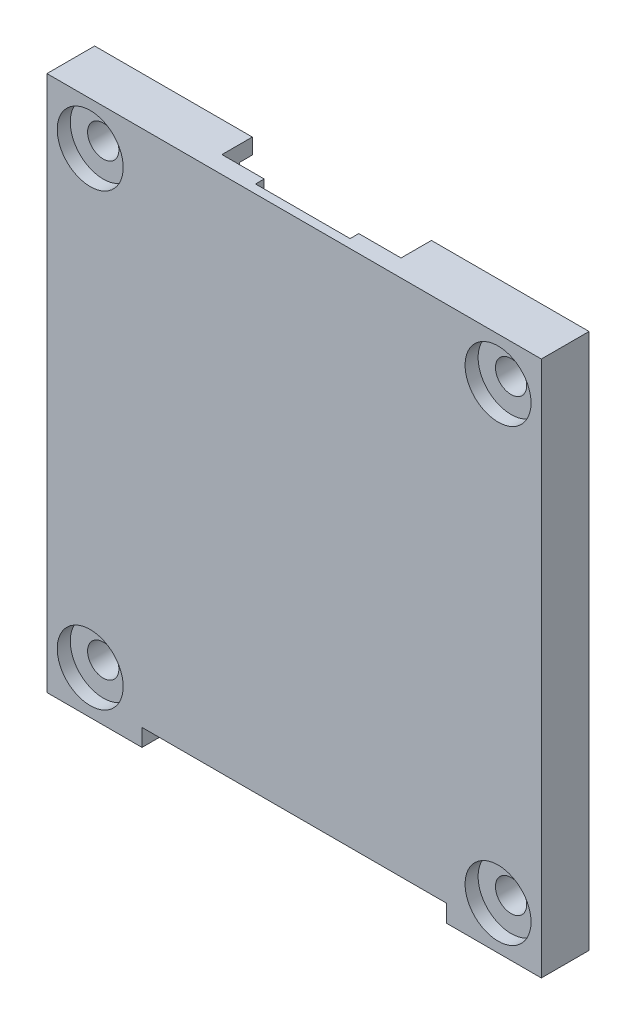
SolidWorks part; units mm, degrees
ref_plane "前视基准面" through (0, 0, 0) normal (0, 0, 1) x (1, 0, 0)
ref_plane "上视基准面" through (0, 0, 0) normal (0, 1, 0) x (1, 0, 0)
ref_plane "右视基准面" through (0, 0, 0) normal (1, 0, 0) x (0, 0, -1)
other "Configuration Table"
sketch "草图1" plane through (0, 0, 0) normal (0, 0, 1) x (1, 0, 0)
  line L1 (-24.5491, 28.8784) -> (32.4256, 28.8784)
  line L2 (-24.5491, 28.8784) -> (-24.5491, -32.8963)
  line L3 (-24.5491, -32.8963) -> (32.4256, -32.8963)
  line L4 (32.4256, 28.8784) -> (32.4256, -32.8963)
  dimension "D1" = 2
  dimension "D2" = 2
  dimension "D3" = 2
  dimension "D4" = 2
extrude "凸台-拉伸1" add sketch "草图1" along normal blind 4
sketch "草图2" plane through (0, 0, 0) normal (0, 0, -1) x (-1, 0, 0)
  line L0 (-14.2579, 28.8784) -> (-9.3875, 28.8784)
  line L1 (-32.4256, 28.8784) -> (24.5491, 28.8784) construction
  line L2 (-9.3875, 28.8784) -> (-9.3875, 24.5138) construction
  line L3 (-9.3875, 28.8784) -> (-9.3875, 24.5138)
  line L5 (-14.2579, 24.5138) -> (-14.2579, 28.8784)
  line L6 (1.511, 28.8784) -> (6.3814, 28.8784)
  line L7 (1.511, 28.8784) -> (1.511, 24.4884) construction
  line L8 (6.3814, 24.4884) -> (6.3814, 28.8784) construction
  line L9 (6.3814, 28.8784) -> (6.3814, 24.4884)
  line L11 (1.511, 24.4884) -> (1.511, 28.8784)
  line L12 (-10.1009, 23.8082) -> (-10.1009, 21.974) construction
  line L14 (1.9244, 24.0844) -> (1.9244, 21.5978)
  line L15 (1.9244, 21.5978) -> (6.1991, 21.5978)
  line L16 (6.1991, 24.0844) -> (6.1991, 21.5978)
  line L18 (-14.0756, 24.0844) -> (-14.0756, 21.5978)
  line L19 (-14.0756, 21.5978) -> (-9.8009, 21.5978)
  line L20 (-9.8009, 24.0844) -> (-9.8009, 21.5978)
  line L21 (-13.7756, 21.974) -> (-13.7756, 23.8082) construction
  line L22 (-10.1771, 21.8978) -> (-11.4621, 21.8978) construction
  line L26 (5.8229, 21.8978) -> (4.538, 21.8978) construction
  line L29 (1.9244, 24.0844) -> (6.1991, 24.0844)
  line L30 (2.3006, 23.8844) -> (3.5856, 23.8844) construction
  line L31 (1.511, 24.4884) -> (6.3814, 24.4884)
  line L32 (3.743, 24.6884) -> (2.219, 24.6884) construction
  line L33 (2.2244, 21.974) -> (2.2244, 23.8082) construction
  line L34 (5.8991, 23.8082) -> (5.8991, 21.974) construction
  line L35 (-14.0756, 24.0844) -> (-9.8009, 24.0844)
  line L36 (-13.6994, 23.8844) -> (-12.4145, 23.8844) construction
  line L37 (-14.2579, 24.5138) -> (-9.3875, 24.5138)
  dimension "D1" = 0.3
  dimension "D2" = 0.3
  dimension "D3" = 0.3
  dimension "D4" = 0.2
  dimension "D5" = 0.2
  dimension "D6" = 0.3
  dimension "D7" = 0.3
  dimension "D8" = 0.3
  dimension "D9" = 0.2
extrude "切除-拉伸1" cut sketch "草图2" along normal blind 0.2 and the other way blind 2
sketch "草图3" plane through (0, 0, 0) normal (0, 0, -1) x (-1, 0, 0)
  line L1 (-9.3875, 20.2641) -> (1.511, 20.2641)
  line L3 (-2.8028, 20.5641) -> (-5.0888, 20.5641) construction
  line L7 (-9.3875, 20.2641) -> (-9.3875, 28.8784)
  line L8 (-9.3875, 28.8784) -> (1.511, 28.8784)
  line L9 (1.511, 28.8784) -> (1.511, 20.2641)
  dimension "D1" = 0.3
extrude "切除-拉伸2" cut sketch "草图3" against normal blind 3
sketch "草图4" plane through (0, 0, 0) normal (0, 0, -1) x (-1, 0, 0)
  line L0 (-8.8148, 20.2641) -> (-8.8148, 14.9345)
  line L1 (-9.3875, 20.2641) -> (1.511, 20.2641) construction
  line L2 (-8.8148, 14.9345) -> (0.9383, 14.9345)
  line L3 (0.9383, 14.9345) -> (0.9383, 20.2641)
  line L4 (0.9383, 20.2641) -> (-8.8148, 20.2641)
  line L5 (-8.5148, 18.6911) -> (-8.5148, 15.4911) construction
  line L6 (0.6383, 15.4911) -> (0.6383, 16.4024) construction
  line L7 (-0.6382, 15.2345) -> (0.3818, 15.2345) construction
  dimension "D1" = 0.3
  dimension "D2" = 0.3
  dimension "D3" = 0.3
extrude "切除-拉伸3" cut sketch "草图4" against normal blind 2
sketch "草图5" plane through (0, 0, 0) normal (0, 0, -1) x (-1, 0, 0)
  circle A0 centre (-22.4383, 24.3411) radius 1.0565 construction
  circle A1 centre (-17.4383, 24.3411) radius 1.0565 construction
  circle A2 centre (-23.4383, 21.841) radius 1.1565 construction
  circle A3 centre (-16.4383, 21.841) radius 1.1565 construction
  circle A4 centre (9.5618, 24.3411) radius 1.0565 construction
  circle A5 centre (14.5618, 24.3411) radius 1.0565 construction
  circle A6 centre (8.5618, 21.841) radius 1.1565 construction
  circle A7 centre (15.5618, 21.841) radius 1.1565 construction
  circle A8 centre (-22.4383, 24.3411) radius 1.35
  circle A9 centre (-23.4383, 21.841) radius 1.5
  circle A10 centre (-17.4383, 24.3411) radius 1.35
  circle A11 centre (-16.4383, 21.841) radius 1.5
  circle A12 centre (9.5618, 24.3411) radius 1.35
  circle A13 centre (8.5618, 21.841) radius 1.5
  circle A14 centre (14.5618, 24.3411) radius 1.35
  circle A15 centre (15.5618, 21.841) radius 1.5
  dimension "D1" = 2.7
  dimension "D2" = 3
  dimension "D3" = 2.7
  dimension "D4" = 3
  dimension "D5" = 2.7
  dimension "D6" = 2.7
  dimension "D7" = 3
  dimension "D8" = 3
extrude "切除-拉伸4" cut sketch "草图5" against normal blind 2 contours A11 A10 | A10 A11 | A10 A11 | A9 A8 | A8 A9 | A8 A9 | A13 A12 | A15 A14 | A12 A13 | A12 A13 | A14 A15 | A14 A15
sketch "草图6" plane through (0, 0, 0) normal (0, 0, -1) x (-1, 0, 0)
  line L1 (19.3218, 20.1001) -> (22.5491, 20.1001)
  line L2 (19.3218, 20.1001) -> (19.3218, -1.154)
  line L3 (19.3218, -1.154) -> (22.5491, -1.154)
  line L4 (22.5491, 20.1001) -> (22.5491, -1.154)
  line L5 (-30.4256, 20.1001) -> (-27.1983, 20.1001)
  line L6 (-30.4256, 20.1001) -> (-30.4256, -1.154)
  line L7 (-30.4256, -1.154) -> (-27.1983, -1.154)
  line L8 (-27.1983, 20.1001) -> (-27.1983, -1.154)
extrude "切除-拉伸5" cut sketch "草图6" against normal blind 2
sketch "草图7" plane through (0, 0, 0) normal (0, 0, -1) x (-1, 0, 0)
  line L0 (6.711, -30.5278) -> (6.711, -29.2577) construction
  line L1 (9.538, -25.4157) -> (10.8229, -25.4157) construction
  line L2 (11.2048, -13.659) -> (12.4048, -13.659)
  line L3 (12.4048, -12.5589) -> (11.2048, -12.5589)
  line L4 (11.2048, -13.659) -> (12.4048, -13.659) construction
  line L5 (12.4048, -12.5589) -> (11.2048, -12.5589) construction
  line L6 (11.2048, -18.459) -> (12.4048, -18.459)
  line L7 (12.4048, -17.359) -> (11.2048, -17.359)
  line L8 (11.2048, -18.459) -> (12.4048, -18.459) construction
  line L9 (12.4048, -17.359) -> (11.2048, -17.359) construction
  line L10 (11.2048, -23.259) -> (12.4048, -23.259)
  line L11 (12.4048, -22.159) -> (11.2048, -22.159)
  line L12 (11.2048, -23.259) -> (12.4048, -23.259) construction
  line L13 (12.4048, -22.159) -> (11.2048, -22.159) construction
  line L14 (7.3006, -25.4157) -> (8.5856, -25.4157) construction
  line L15 (8.5856, -27.4023) -> (7.3006, -27.4023) construction
  line L16 (13.4048, -21.859) -> (10.2048, -21.859)
  line L17 (13.4048, -23.559) -> (13.4048, -21.859)
  line L18 (10.2048, -23.559) -> (13.4048, -23.559)
  line L19 (10.2048, -21.859) -> (10.2048, -23.559)
  line L20 (13.4048, -21.859) -> (10.2048, -21.859)
  line L21 (13.4048, -23.559) -> (13.4048, -21.859)
  line L22 (10.2048, -23.559) -> (13.4048, -23.559)
  line L23 (10.2048, -21.859) -> (10.2048, -23.559)
  line L24 (13.4048, -17.059) -> (10.2048, -17.059)
  line L25 (13.4048, -18.759) -> (13.4048, -17.059)
  line L26 (10.2048, -18.759) -> (13.4048, -18.759)
  line L27 (10.2048, -17.059) -> (10.2048, -18.759)
  line L28 (13.4048, -17.059) -> (10.2048, -17.059)
  line L29 (13.4048, -18.759) -> (13.4048, -17.059)
  line L30 (10.2048, -18.759) -> (13.4048, -18.759)
  line L31 (10.2048, -17.059) -> (10.2048, -18.759)
  line L32 (13.4048, -12.2589) -> (10.2048, -12.2589)
  line L33 (13.4048, -13.959) -> (13.4048, -12.2589)
  line L34 (10.2048, -13.959) -> (13.4048, -13.959)
  line L35 (10.2048, -12.2589) -> (10.2048, -13.959)
  line L36 (13.4048, -12.2589) -> (10.2048, -12.2589)
  line L37 (13.4048, -13.959) -> (13.4048, -12.2589)
  line L38 (10.2048, -13.959) -> (13.4048, -13.959)
  line L39 (10.2048, -12.2589) -> (10.2048, -13.959)
  line L40 (7.2244, -27.3261) -> (7.2244, -25.4919) construction
  line L41 (10.8991, -25.4919) -> (10.8991, -27.3261) construction
  line L42 (11.1814, -28.8767) -> (11.1814, -30.8963) construction
  line L43 (9.505, -28.7497) -> (11.0544, -28.7497) construction
  line L44 (7.2444, -28.7243) -> (8.7176, -28.7243) construction
  line L45 (-18.6994, -25.4157) -> (-17.4145, -25.4157) construction
  line L46 (-18.7756, -27.3261) -> (-18.7756, -25.4919) construction
  line L47 (-15.1009, -25.4919) -> (-15.1009, -27.3261) construction
  line L48 (-17.4145, -27.4023) -> (-18.6994, -27.4023) construction
  line L49 (-16.6195, -28.7523) -> (-15.0955, -28.7523) construction
  line L50 (-19.0579, -30.8963) -> (-19.0579, -28.8793) construction
  line L51 (-14.5875, -29.2603) -> (-14.5875, -30.5303) construction
  line L52 (6.711, -30.5278) -> (6.711, -29.2577)
  line L53 (9.538, -25.4157) -> (10.8229, -25.4157)
  line L54 (7.3006, -25.4157) -> (8.5856, -25.4157)
  line L55 (8.5856, -27.4023) -> (7.3006, -27.4023)
  line L56 (7.2244, -27.3261) -> (7.2244, -25.4919)
  line L57 (10.8991, -25.4919) -> (10.8991, -27.3261)
  line L58 (11.1814, -28.8767) -> (11.1814, -30.8963)
  line L59 (9.505, -28.7497) -> (11.0544, -28.7497)
  line L60 (7.2444, -28.7243) -> (8.7176, -28.7243)
  line L61 (-18.6994, -25.4157) -> (-17.4145, -25.4157)
  line L62 (-18.7756, -27.3261) -> (-18.7756, -25.4919)
  line L63 (-15.1009, -25.4919) -> (-15.1009, -27.3261)
  line L64 (-17.4145, -27.4023) -> (-18.6994, -27.4023)
  line L65 (-16.6195, -28.7523) -> (-15.0955, -28.7523)
  line L66 (-19.0579, -30.8963) -> (-19.0579, -28.8793)
  line L67 (-14.5875, -29.2603) -> (-14.5875, -30.5303)
  circle A1 centre (11.0544, -4.4087) radius 0.9
  circle A2 centre (11.0544, -4.4087) radius 0.9
  circle A3 centre (-1.4384, -17.8159) radius 1.55
  circle A4 centre (-1.4384, -17.8159) radius 1.55
  circle A5 centre (11.0544, -9.4088) radius 0.9
  circle A6 centre (11.0544, -9.4088) radius 0.9
  circle A7 centre (-6.4382, -17.816) radius 1.55
  circle A8 centre (-6.4382, -17.816) radius 1.55
  circle A12 centre (-9.4382, -27.816) radius 1.3
  circle A13 centre (1.5618, -27.816) radius 1.3
  spline S0 degree 2 poles (1678.0415, 1065.4937) (11.9563, -51.0686) (-2.5809, -18.3227) (-2.6751, -18.1106) (-2.6867, -17.8776) (-2.6983, -17.6458) (-2.6253, -17.4243) (-2.5527, -17.2039) (-2.4049, -17.0235) (-2.2578, -16.8439) (-2.055, -16.7288) (-1.8532, -16.6142) (-1.6226, -16.5797) (-1.393, -16.5453) (-1.1654, -16.5961) (33.6716, -24.3719) (-710.0576, -1886.511) knots -19.102519 -19.102519 -19.102519 0.125 0.125 0.25 0.25 0.375 0.375 0.5 0.5 0.625 0.625 0.75 0.75 0.875 0.875 20.074642 20.074642 20.074642 only from (-2.3221, -18.6999) to (-0.7448, -16.776) construction
  spline S1 degree 2 poles (1902.7481, -608.804) (-22.9104, -49.606) (-7.5673, -17.2795) (-7.475, -17.0851) (-7.3221, -16.9321) (-7.17, -16.7799) (-6.9747, -16.687) (25.2074, -1.3776) (613.4226, -1917.7837) knots -41.164672 -41.164672 -41.164672 0.25 0.25 0.5 0.5 0.75 0.75 42.09914 42.09914 42.09914 only from (-7.6818, -17.689) to (-6.5652, -16.5725) construction
  spline S2 degree 2 poles (2950.6338, 591.2484) (-0.0165, 21.11) (10.5998, -4.6) (10.6376, -4.6914) (10.7082, -4.7622) (10.7781, -4.8322) (10.8704, -4.8706) (10.9618, -4.9086) (11.0618, -4.9087) (11.1607, -4.9088) (11.2531, -4.8706) (11.3445, -4.8329) (11.4153, -4.7622) (11.4854, -4.6924) (11.5237, -4.6) (22.1068, 20.8706) (-2910.0665, 675.7824) knots -34.741877 -34.741877 -34.741877 0.125 0.125 0.25 0.25 0.375 0.375 0.5 0.5 0.625 0.625 0.75 0.75 0.875 0.875 35.632733 35.632733 35.632733 only from (10.5618, -4.4087) to (11.5618, -4.4087)
  spline S3 degree 2 poles (-2928.5103, -600.0658) (22.1401, -29.9274) (11.5237, -4.2173) (11.486, -4.1259) (11.4153, -4.0551) (11.3455, -3.9851) (11.2531, -3.9467) (11.1618, -3.9088) (11.0618, -3.9087) (10.9629, -3.9086) (10.8704, -3.9467) (10.779, -3.9845) (10.7082, -4.0551) (10.6382, -4.125) (10.5998, -4.2173) (0.0167, -29.6879) (2932.1901, -684.5997) knots -34.741877 -34.741877 -34.741877 0.125 0.125 0.25 0.25 0.375 0.375 0.5 0.5 0.625 0.625 0.75 0.75 0.875 0.875 35.632733 35.632733 35.632733 only from (11.5618, -4.4087) to (10.5618, -4.4087)
  spline S4 degree 2 poles (10.5618, -4.4087) (10.5618, -4.5078) (10.5998, -4.6) (10.6376, -4.6914) (10.7082, -4.7622) (10.7781, -4.8322) (10.8704, -4.8706) (10.9618, -4.9086) (11.0618, -4.9087) (11.1607, -4.9088) (11.2531, -4.8706) (11.3445, -4.8329) (11.4153, -4.7622) (11.4854, -4.6924) (11.5237, -4.6) (11.5618, -4.5084) (11.5618, -4.4087) knots 0 0 0 0.125 0.125 0.25 0.25 0.375 0.375 0.5 0.5 0.625 0.625 0.75 0.75 0.875 0.875 1 1 1 construction
  spline S5 degree 2 poles (11.5618, -4.4087) (11.5618, -4.3095) (11.5237, -4.2173) (11.486, -4.1259) (11.4153, -4.0551) (11.3455, -3.9851) (11.2531, -3.9467) (11.1618, -3.9088) (11.0618, -3.9087) (10.9629, -3.9086) (10.8704, -3.9467) (10.779, -3.9845) (10.7082, -4.0551) (10.6382, -4.125) (10.5998, -4.2173) (10.5618, -4.3089) (10.5618, -4.4087) knots 0 0 0 0.125 0.125 0.25 0.25 0.375 0.375 0.5 0.5 0.625 0.625 0.75 0.75 0.875 0.875 1 1 1 construction
  spline S6 degree 2 poles (2950.6338, 586.2483) (-0.0165, 16.1099) (10.5998, -9.6001) (10.6376, -9.6915) (10.7082, -9.7623) (10.7781, -9.8323) (10.8704, -9.8707) (10.9618, -9.9087) (11.0618, -9.9088) (11.1607, -9.9089) (11.2531, -9.8707) (11.3445, -9.833) (11.4153, -9.7623) (11.4854, -9.6925) (11.5237, -9.6001) (22.1068, 15.8705) (-2910.0665, 670.7823) knots -34.741877 -34.741877 -34.741877 0.125 0.125 0.25 0.25 0.375 0.375 0.5 0.5 0.625 0.625 0.75 0.75 0.875 0.875 35.632733 35.632733 35.632733 only from (10.5618, -9.4088) to (11.5618, -9.4088)
  spline S7 degree 2 poles (-2928.5103, -605.0659) (22.1401, -34.9275) (11.5237, -9.2174) (11.486, -9.126) (11.4153, -9.0552) (11.3455, -8.9852) (11.2531, -8.9468) (11.1618, -8.9089) (11.0618, -8.9088) (10.9629, -8.9087) (10.8704, -8.9468) (10.779, -8.9846) (10.7082, -9.0552) (10.6382, -9.1251) (10.5998, -9.2174) (0.0167, -34.688) (2932.1901, -689.5998) knots -34.741877 -34.741877 -34.741877 0.125 0.125 0.25 0.25 0.375 0.375 0.5 0.5 0.625 0.625 0.75 0.75 0.875 0.875 35.632733 35.632733 35.632733 only from (11.5618, -9.4088) to (10.5618, -9.4088)
  spline S8 degree 2 poles (10.5618, -9.4088) (10.5618, -9.5079) (10.5998, -9.6001) (10.6376, -9.6915) (10.7082, -9.7623) (10.7781, -9.8323) (10.8704, -9.8707) (10.9618, -9.9087) (11.0618, -9.9088) (11.1607, -9.9089) (11.2531, -9.8707) (11.3445, -9.833) (11.4153, -9.7623) (11.4854, -9.6925) (11.5237, -9.6001) (11.5618, -9.5085) (11.5618, -9.4088) knots 0 0 0 0.125 0.125 0.25 0.25 0.375 0.375 0.5 0.5 0.625 0.625 0.75 0.75 0.875 0.875 1 1 1 construction
  spline S9 degree 2 poles (11.5618, -9.4088) (11.5618, -9.3096) (11.5237, -9.2174) (11.486, -9.126) (11.4153, -9.0552) (11.3455, -8.9852) (11.2531, -8.9468) (11.1618, -8.9089) (11.0618, -8.9088) (10.9629, -8.9087) (10.8704, -8.9468) (10.779, -8.9846) (10.7082, -9.0552) (10.6382, -9.1251) (10.5998, -9.2174) (10.5618, -9.309) (10.5618, -9.4088) knots 0 0 0 0.125 0.125 0.25 0.25 0.375 0.375 0.5 0.5 0.625 0.625 0.75 0.75 0.875 0.875 1 1 1 construction
  spline S10 degree 2 poles (-589.7302, 2925.0534) (-14.3408, -24.7511) (12.6153, -13.6171) (12.7159, -13.5755) (12.7937, -13.4979) (12.8708, -13.421) (12.9129, -13.3194) (12.9547, -13.2189) (12.9548, -13.1089) (12.9549, -13.0001) (12.9129, -12.8985) (12.8714, -12.7979) (12.7937, -12.72) (12.7168, -12.643) (12.6153, -12.6008) (-14.1125, -1.4985) (-666.5698, -2934.5065) knots -33.117037 -33.117037 -33.117037 0.125 0.125 0.25 0.25 0.375 0.375 0.5 0.5 0.625 0.625 0.75 0.75 0.875 0.875 34.022438 34.022438 34.022438 only from (12.4048, -13.659) to (12.4048, -12.5589)
  spline S11 degree 2 poles (613.3398, -2951.2713) (37.9504, -1.4668) (10.9943, -12.6008) (10.8937, -12.6424) (10.8159, -12.72) (10.7389, -12.7969) (10.6967, -12.8985) (10.6549, -12.999) (10.6548, -13.1089) (10.6547, -13.2178) (10.6967, -13.3194) (10.7382, -13.42) (10.8159, -13.4979) (10.8928, -13.5749) (10.9943, -13.6171) (37.7221, -24.7194) (690.1794, 2908.2886) knots -33.117037 -33.117037 -33.117037 0.125 0.125 0.25 0.25 0.375 0.375 0.5 0.5 0.625 0.625 0.75 0.75 0.875 0.875 34.022438 34.022438 34.022438 only from (11.2048, -12.5589) to (11.2048, -13.659)
  spline S12 degree 2 poles (12.4048, -13.659) (12.5139, -13.659) (12.6153, -13.6171) (12.7159, -13.5755) (12.7937, -13.4979) (12.8708, -13.421) (12.9129, -13.3194) (12.9547, -13.2189) (12.9548, -13.1089) (12.9549, -13.0001) (12.9129, -12.8985) (12.8714, -12.7979) (12.7937, -12.72) (12.7168, -12.643) (12.6153, -12.6008) (12.5145, -12.5589) (12.4048, -12.5589) knots 0 0 0 0.125 0.125 0.25 0.25 0.375 0.375 0.5 0.5 0.625 0.625 0.75 0.75 0.875 0.875 1 1 1 construction
  spline S13 degree 2 poles (11.2048, -12.5589) (11.0957, -12.5589) (10.9943, -12.6008) (10.8937, -12.6424) (10.8159, -12.72) (10.7389, -12.7969) (10.6967, -12.8985) (10.6549, -12.999) (10.6548, -13.1089) (10.6547, -13.2178) (10.6967, -13.3194) (10.7382, -13.42) (10.8159, -13.4979) (10.8928, -13.5749) (10.9943, -13.6171) (11.0951, -13.659) (11.2048, -13.659) knots 0 0 0 0.125 0.125 0.25 0.25 0.375 0.375 0.5 0.5 0.625 0.625 0.75 0.75 0.875 0.875 1 1 1 construction
  spline S14 degree 2 poles (-589.7302, 2920.2534) (-14.3408, -29.5511) (12.6153, -18.4171) (12.7159, -18.3756) (12.7937, -18.2979) (12.8708, -18.221) (12.9129, -18.1195) (12.9547, -18.0189) (12.9548, -17.909) (12.9549, -17.8001) (12.9129, -17.6985) (12.8714, -17.5979) (12.7937, -17.5201) (12.7168, -17.443) (12.6153, -17.4008) (-14.1125, -6.2985) (-666.5698, -2939.3065) knots -33.117037 -33.117037 -33.117037 0.125 0.125 0.25 0.25 0.375 0.375 0.5 0.5 0.625 0.625 0.75 0.75 0.875 0.875 34.022438 34.022438 34.022438 only from (12.4048, -18.459) to (12.4048, -17.359)
  spline S15 degree 2 poles (613.3398, -2956.0713) (37.9504, -6.2668) (10.9943, -17.4008) (10.8937, -17.4424) (10.8159, -17.5201) (10.7389, -17.5969) (10.6967, -17.6985) (10.6549, -17.799) (10.6548, -17.909) (10.6547, -18.0178) (10.6967, -18.1195) (10.7382, -18.2201) (10.8159, -18.2979) (10.8928, -18.3749) (10.9943, -18.4171) (37.7221, -29.5194) (690.1794, 2903.4885) knots -33.117037 -33.117037 -33.117037 0.125 0.125 0.25 0.25 0.375 0.375 0.5 0.5 0.625 0.625 0.75 0.75 0.875 0.875 34.022438 34.022438 34.022438 only from (11.2048, -17.359) to (11.2048, -18.459)
  spline S16 degree 2 poles (12.4048, -18.459) (12.5139, -18.459) (12.6153, -18.4171) (12.7159, -18.3756) (12.7937, -18.2979) (12.8708, -18.221) (12.9129, -18.1195) (12.9547, -18.0189) (12.9548, -17.909) (12.9549, -17.8001) (12.9129, -17.6985) (12.8714, -17.5979) (12.7937, -17.5201) (12.7168, -17.443) (12.6153, -17.4008) (12.5145, -17.359) (12.4048, -17.359) knots 0 0 0 0.125 0.125 0.25 0.25 0.375 0.375 0.5 0.5 0.625 0.625 0.75 0.75 0.875 0.875 1 1 1 construction
  spline S17 degree 2 poles (11.2048, -17.359) (11.0957, -17.359) (10.9943, -17.4008) (10.8937, -17.4424) (10.8159, -17.5201) (10.7389, -17.5969) (10.6967, -17.6985) (10.6549, -17.799) (10.6548, -17.909) (10.6547, -18.0178) (10.6967, -18.1195) (10.7382, -18.2201) (10.8159, -18.2979) (10.8928, -18.3749) (10.9943, -18.4171) (11.0951, -18.459) (11.2048, -18.459) knots 0 0 0 0.125 0.125 0.25 0.25 0.375 0.375 0.5 0.5 0.625 0.625 0.75 0.75 0.875 0.875 1 1 1 construction
  spline S18 degree 2 poles (-589.7302, 2915.4534) (-14.3408, -34.3511) (12.6153, -23.2171) (12.7159, -23.1756) (12.7937, -23.0979) (12.8708, -23.021) (12.9129, -22.9195) (12.9547, -22.8189) (12.9548, -22.709) (12.9549, -22.6001) (12.9129, -22.4985) (12.8714, -22.3979) (12.7937, -22.3201) (12.7168, -22.243) (12.6153, -22.2008) (-14.1125, -11.0985) (-666.5698, -2944.1065) knots -33.117037 -33.117037 -33.117037 0.125 0.125 0.25 0.25 0.375 0.375 0.5 0.5 0.625 0.625 0.75 0.75 0.875 0.875 34.022438 34.022438 34.022438 only from (12.4048, -23.259) to (12.4048, -22.159)
  spline S19 degree 2 poles (613.3398, -2960.8713) (37.9504, -11.0668) (10.9943, -22.2008) (10.8937, -22.2424) (10.8159, -22.3201) (10.7389, -22.3969) (10.6967, -22.4985) (10.6549, -22.599) (10.6548, -22.709) (10.6547, -22.8178) (10.6967, -22.9195) (10.7382, -23.0201) (10.8159, -23.0979) (10.8928, -23.1749) (10.9943, -23.2171) (37.7221, -34.3194) (690.1794, 2898.6885) knots -33.117037 -33.117037 -33.117037 0.125 0.125 0.25 0.25 0.375 0.375 0.5 0.5 0.625 0.625 0.75 0.75 0.875 0.875 34.022438 34.022438 34.022438 only from (11.2048, -22.159) to (11.2048, -23.259)
  spline S20 degree 2 poles (12.4048, -23.259) (12.5139, -23.259) (12.6153, -23.2171) (12.7159, -23.1756) (12.7937, -23.0979) (12.8708, -23.021) (12.9129, -22.9195) (12.9547, -22.8189) (12.9548, -22.709) (12.9549, -22.6001) (12.9129, -22.4985) (12.8714, -22.3979) (12.7937, -22.3201) (12.7168, -22.243) (12.6153, -22.2008) (12.5145, -22.159) (12.4048, -22.159) knots 0 0 0 0.125 0.125 0.25 0.25 0.375 0.375 0.5 0.5 0.625 0.625 0.75 0.75 0.875 0.875 1 1 1 construction
  spline S21 degree 2 poles (11.2048, -22.159) (11.0957, -22.159) (10.9943, -22.2008) (10.8937, -22.2424) (10.8159, -22.3201) (10.7389, -22.3969) (10.6967, -22.4985) (10.6549, -22.599) (10.6548, -22.709) (10.6547, -22.8178) (10.6967, -22.9195) (10.7382, -23.0201) (10.8159, -23.0979) (10.8928, -23.1749) (10.9943, -23.2171) (11.0951, -23.259) (11.2048, -23.259) knots 0 0 0 0.125 0.125 0.25 0.25 0.375 0.375 0.5 0.5 0.625 0.625 0.75 0.75 0.875 0.875 1 1 1 construction
  spline S22 degree 2 poles (2922.4089, 651.7628) (-13.4862, 6.1019) (0.7303, -28.1604) (0.7991, -28.3263) (0.9254, -28.4524) (1.0524, -28.5793) (1.2173, -28.6475) (1.3833, -28.7161) (1.5618, -28.716) (1.7413, -28.7159) (1.9062, -28.6475) (2.072, -28.5787) (2.1981, -28.4524) (2.325, -28.3253) (2.3932, -28.1604) (16.635, 6.2818) (-2929.7513, 604.884) knots -25.81424 -25.81424 -25.81424 0.125 0.125 0.25 0.25 0.375 0.375 0.5 0.5 0.625 0.625 0.75 0.75 0.875 0.875 26.860433 26.860433 26.860433 only from (0.6618, -27.816) to (2.4618, -27.816)
  spline S23 degree 2 poles (-2919.2854, -707.3948) (16.6097, -61.7339) (2.3932, -27.4716) (2.3244, -27.3057) (2.1981, -27.1796) (2.0711, -27.0527) (1.9062, -26.9845) (1.7402, -26.9159) (1.5618, -26.916) (1.3822, -26.9161) (1.2173, -26.9845) (1.0515, -27.0533) (0.9254, -27.1796) (0.7985, -27.3067) (0.7303, -27.4716) (-13.5115, -61.9138) (2932.8748, -660.516) knots -25.81424 -25.81424 -25.81424 0.125 0.125 0.25 0.25 0.375 0.375 0.5 0.5 0.625 0.625 0.75 0.75 0.875 0.875 26.860433 26.860433 26.860433 only from (2.4618, -27.816) to (0.6618, -27.816)
  spline S24 degree 2 poles (0.6618, -27.816) (0.6618, -27.9953) (0.7303, -28.1604) (0.7991, -28.3263) (0.9254, -28.4524) (1.0524, -28.5793) (1.2173, -28.6475) (1.3833, -28.7161) (1.5618, -28.716) (1.7413, -28.7159) (1.9062, -28.6475) (2.072, -28.5787) (2.1981, -28.4524) (2.325, -28.3253) (2.3932, -28.1604) (2.4618, -27.9947) (2.4618, -27.816) knots 0 0 0 0.125 0.125 0.25 0.25 0.375 0.375 0.5 0.5 0.625 0.625 0.75 0.75 0.875 0.875 1 1 1 construction
  spline S25 degree 2 poles (2.4618, -27.816) (2.4618, -27.6367) (2.3932, -27.4716) (2.3244, -27.3057) (2.1981, -27.1796) (2.0711, -27.0527) (1.9062, -26.9845) (1.7402, -26.9159) (1.5618, -26.916) (1.3822, -26.9161) (1.2173, -26.9845) (1.0515, -27.0533) (0.9254, -27.1796) (0.7985, -27.3067) (0.7303, -27.4716) (0.6618, -27.6373) (0.6618, -27.816) knots 0 0 0 0.125 0.125 0.25 0.25 0.375 0.375 0.5 0.5 0.625 0.625 0.75 0.75 0.875 0.875 1 1 1 construction
  spline S26 degree 2 poles (2911.4089, 651.7628) (-24.4862, 6.1019) (-10.2697, -28.1604) (-10.2009, -28.3263) (-10.0746, -28.4524) (-9.9476, -28.5793) (-9.7827, -28.6475) (-9.6167, -28.7161) (-9.4382, -28.716) (-9.2587, -28.7159) (-9.0938, -28.6475) (-8.928, -28.5787) (-8.8019, -28.4524) (-8.675, -28.3253) (-8.6068, -28.1604) (5.635, 6.2818) (-2940.7513, 604.884) knots -25.81424 -25.81424 -25.81424 0.125 0.125 0.25 0.25 0.375 0.375 0.5 0.5 0.625 0.625 0.75 0.75 0.875 0.875 26.860433 26.860433 26.860433 only from (-10.3382, -27.816) to (-8.5382, -27.816)
  spline S27 degree 2 poles (-2930.2854, -707.3948) (5.6097, -61.7339) (-8.6068, -27.4716) (-8.6756, -27.3057) (-8.8019, -27.1796) (-8.9289, -27.0527) (-9.0938, -26.9845) (-9.2598, -26.9159) (-9.4382, -26.916) (-9.6178, -26.9161) (-9.7827, -26.9845) (-9.9485, -27.0533) (-10.0746, -27.1796) (-10.2015, -27.3067) (-10.2697, -27.4716) (-24.5115, -61.9138) (2921.8748, -660.516) knots -25.81424 -25.81424 -25.81424 0.125 0.125 0.25 0.25 0.375 0.375 0.5 0.5 0.625 0.625 0.75 0.75 0.875 0.875 26.860433 26.860433 26.860433 only from (-8.5382, -27.816) to (-10.3382, -27.816)
  spline S28 degree 2 poles (-10.3382, -27.816) (-10.3382, -27.9953) (-10.2697, -28.1604) (-10.2009, -28.3263) (-10.0746, -28.4524) (-9.9476, -28.5793) (-9.7827, -28.6475) (-9.6167, -28.7161) (-9.4382, -28.716) (-9.2587, -28.7159) (-9.0938, -28.6475) (-8.928, -28.5787) (-8.8019, -28.4524) (-8.675, -28.3253) (-8.6068, -28.1604) (-8.5382, -27.9947) (-8.5382, -27.816) knots 0 0 0 0.125 0.125 0.25 0.25 0.375 0.375 0.5 0.5 0.625 0.625 0.75 0.75 0.875 0.875 1 1 1 construction
  spline S29 degree 2 poles (-8.5382, -27.816) (-8.5382, -27.6367) (-8.6068, -27.4716) (-8.6756, -27.3057) (-8.8019, -27.1796) (-8.9289, -27.0527) (-9.0938, -26.9845) (-9.2598, -26.9159) (-9.4382, -26.916) (-9.6178, -26.9161) (-9.7827, -26.9845) (-9.9485, -27.0533) (-10.0746, -27.1796) (-10.2015, -27.3067) (-10.2697, -27.4716) (-10.3382, -27.6373) (-10.3382, -27.816) knots 0 0 0 0.125 0.125 0.25 0.25 0.375 0.375 0.5 0.5 0.625 0.625 0.75 0.75 0.875 0.875 1 1 1 construction
  spline S30 degree 2 poles (-597.4262, -1927.0024) (-38.2283, -1.3438) (-5.9018, -16.687) (-5.7074, -16.7793) (-5.5544, -16.9321) (-5.4021, -17.0842) (-5.3092, -17.2795) (10.0001, -49.4617) (-1906.406, -637.6769) knots -41.164672 -41.164672 -41.164672 0.25 0.25 0.5 0.5 0.75 0.75 42.09914 42.09914 42.09914 only from (-6.3112, -16.5725) to (-5.1947, -17.689) construction
  spline S31 degree 2 poles (-1915.6246, 573.172) (10.0339, 13.974) (-5.3092, -18.3525) (-5.4015, -18.5469) (-5.5544, -18.6999) (-5.7065, -18.8521) (-5.9018, -18.945) (-38.0839, -34.2544) (-626.2991, 1882.1517) knots -41.164672 -41.164672 -41.164672 0.25 0.25 0.5 0.5 0.75 0.75 42.09914 42.09914 42.09914 only from (-5.1947, -17.943) to (-6.3112, -19.0595) construction
  spline S32 degree 2 poles (584.5497, 1891.3704) (25.3518, -34.2882) (-6.9747, -18.945) (-7.1691, -18.8528) (-7.3221, -18.6999) (-7.4744, -18.5478) (-7.5673, -18.3525) (-22.8766, 13.8297) (1893.5295, 602.0449) knots -41.164672 -41.164672 -41.164672 0.25 0.25 0.5 0.5 0.75 0.75 42.09914 42.09914 42.09914 only from (-6.5652, -19.0595) to (-7.6818, -17.943) construction
  spline S33 degree 2 poles (-2.3221, -18.6999) (-2.4864, -18.5356) (-2.5809, -18.3227) (-2.6751, -18.1106) (-2.6867, -17.8776) (-2.6983, -17.6458) (-2.6253, -17.4243) (-2.5527, -17.2039) (-2.4049, -17.0235) (-2.2578, -16.8439) (-2.055, -16.7288) (-1.8532, -16.6142) (-1.6226, -16.5797) (-1.393, -16.5453) (-1.1654, -16.5961) (-0.9386, -16.6468) (-0.7448, -16.776) knots 0 0 0 0.125 0.125 0.25 0.25 0.375 0.375 0.5 0.5 0.625 0.625 0.75 0.75 0.875 0.875 1 1 1 construction
  spline S34 degree 2 poles (-7.6818, -17.689) (-7.6599, -17.4747) (-7.5673, -17.2795) (-7.475, -17.0851) (-7.3221, -16.9321) (-7.17, -16.7799) (-6.9747, -16.687) (-6.7801, -16.5944) (-6.5652, -16.5725) knots 0 0 0 0.25 0.25 0.5 0.5 0.75 0.75 1 1 1 construction
  spline S35 degree 2 poles (-6.3112, -16.5725) (-6.0969, -16.5944) (-5.9018, -16.687) (-5.7074, -16.7793) (-5.5544, -16.9321) (-5.4021, -17.0842) (-5.3092, -17.2795) (-5.2167, -17.4741) (-5.1947, -17.689) knots 0 0 0 0.25 0.25 0.5 0.5 0.75 0.75 1 1 1 construction
  spline S36 degree 2 poles (-5.1947, -17.943) (-5.2166, -18.1573) (-5.3092, -18.3525) (-5.4015, -18.5469) (-5.5544, -18.6999) (-5.7065, -18.8521) (-5.9018, -18.945) (-6.0963, -19.0376) (-6.3112, -19.0595) knots 0 0 0 0.25 0.25 0.5 0.5 0.75 0.75 1 1 1 construction
  spline S37 degree 2 poles (-6.5652, -19.0595) (-6.7796, -19.0376) (-6.9747, -18.945) (-7.1691, -18.8528) (-7.3221, -18.6999) (-7.4744, -18.5478) (-7.5673, -18.3525) (-7.6598, -18.1579) (-7.6818, -17.943) knots 0 0 0 0.25 0.25 0.5 0.5 0.75 0.75 1 1 1 construction
  dimension "D15" = 2.6
  dimension "D16" = 2.6
  dimension "D1" = 0
  dimension "D2" = 0
  dimension "D3" = 0
  dimension "D4" = 0
  dimension "D5" = 0
  dimension "D6" = 0
  dimension "D7" = 0
  dimension "D8" = 0
  dimension "D9" = 0
  dimension "D10" = 0
  dimension "D11" = 0
  dimension "D12" = 0
  dimension "D13" = 0
  dimension "D14" = 0
extrude "切除-拉伸8" cut sketch "草图7" against normal blind 3 contours A4 | A8 | A12 | A13 | A2 | A6 | L36 L39 L38 L37 | L28 L31 L30 L29 | L20 L23 L22 L21
sketch "草图9" plane through (0, 0, 0) normal (0, 0, -1) x (-1, 0, 0)
  line L0 (24.5491, -32.8963) -> (-32.4256, -32.8963) construction
  line L1 (6.9244, -25.1157) -> (11.1991, -25.1157)
  line L2 (6.9244, -25.1157) -> (6.9244, -27.7023)
  line L3 (6.9244, -27.7023) -> (11.1991, -27.7023)
  line L4 (11.1991, -25.1157) -> (11.1991, -27.7023)
  line L5 (6.411, -28.4243) -> (11.4814, -28.4243)
  line L6 (6.411, -28.4243) -> (6.411, -32.8963)
  line L7 (6.411, -32.8963) -> (11.4814, -32.8963)
  line L8 (11.4814, -28.4243) -> (11.4814, -32.8963)
  line L9 (8.5856, -27.4023) -> (7.3006, -27.4023) construction
  line L10 (-19.0756, -25.1157) -> (-14.8009, -25.1157)
  line L11 (-19.0756, -25.1157) -> (-19.0756, -27.7023)
  line L12 (-19.0756, -27.7023) -> (-14.8009, -27.7023)
  line L13 (-14.8009, -25.1157) -> (-14.8009, -27.7023)
  line L14 (-19.3579, -28.4523) -> (-14.2875, -28.4523)
  line L15 (-19.3579, -28.4523) -> (-19.3579, -32.8963)
  line L16 (-19.3579, -32.8963) -> (-14.2875, -32.8963)
  line L17 (-14.2875, -28.4523) -> (-14.2875, -32.8963)
  line L18 (7.3006, -25.4157) -> (8.5856, -25.4157) construction
  line L19 (10.8991, -25.4919) -> (10.8991, -27.3261) construction
  line L20 (7.2244, -27.3261) -> (7.2244, -25.4919) construction
  line L21 (-15.1009, -25.4919) -> (-15.1009, -27.3261) construction
  line L22 (-18.7756, -27.3261) -> (-18.7756, -25.4919) construction
  line L23 (-18.6994, -25.4157) -> (-17.4145, -25.4157) construction
  line L24 (-17.4145, -27.4023) -> (-18.6994, -27.4023) construction
  line L25 (-16.6195, -28.7523) -> (-15.0955, -28.7523) construction
  line L26 (-14.5875, -29.2603) -> (-14.5875, -30.5303) construction
  line L27 (-19.0579, -30.8963) -> (-19.0579, -28.8793) construction
  line L28 (11.1814, -28.8767) -> (11.1814, -30.8963) construction
  line L29 (6.711, -30.5278) -> (6.711, -29.2577) construction
  line L30 (7.2444, -28.7243) -> (8.7176, -28.7243) construction
  dimension "D1" = 0.3
  dimension "D2" = 0.3
  dimension "D3" = 0.3
  dimension "D4" = 0.3
  dimension "D5" = 0.3
  dimension "D6" = 0.3
  dimension "D7" = 0.3
  dimension "D8" = 0.3
  dimension "D9" = 0.3
  dimension "D10" = 0.3
  dimension "D11" = 0.3
  dimension "D12" = 0.3
  dimension "D13" = 0.3
  dimension "D14" = 0.3
extrude "切除-拉伸9" cut sketch "草图9" against normal blind 2
sketch "草图10" plane through (0, 0, 0) normal (0, 0, -1) x (-1, 0, 0)
  line L0 (24.5491, -32.8963) -> (11.4814, -32.8963) construction
  line L1 (-21.4697, -30.8963) -> (13.5934, -30.8963)
  line L2 (-21.4697, -30.8963) -> (-21.4697, -32.8963)
  line L3 (-21.4697, -32.8963) -> (13.5934, -32.8963)
  line L4 (13.5934, -30.8963) -> (13.5934, -32.8963)
  line L5 (13.5934, -30.8963) -> (13.5934, -32.8963) construction
extrude "切除-拉伸10" cut sketch "草图10" against normal through all
sketch "草图11" plane through (0, 0, 0) normal (0, 0, -1) x (-1, 0, 0)
  line L1 (6.3814, 28.8784) -> (24.5491, 28.8784)
  line L2 (-32.4256, 28.8784) -> (-32.4256, -32.8963)
  line L3 (-32.4256, -32.8963) -> (-21.4697, -32.8963)
  line L4 (24.5491, 28.8784) -> (24.5491, -32.8963)
  line L5 (-21.4697, -30.8963) -> (-21.4697, -32.8963) construction
  line L6 (-22.3697, -32.0963) -> (-31.6256, -32.0963)
  line L11 (-31.6256, -32.0963) -> (-31.6256, -3.619)
  line L12 (-31.6256, 28.0784) -> (-24.9152, 28.0784)
  line L13 (23.7491, 28.0784) -> (23.7491, -10.3319)
  line L14 (23.7491, -32.0963) -> (14.4934, -32.0963)
  line L15 (13.5934, -32.8963) -> (13.5934, -30.8963) construction
  line L17 (13.5934, -32.8963) -> (24.5491, -32.8963)
  line L19 (-14.2579, 28.8784) -> (-14.2579, 27.0784)
  line L20 (-14.2579, 24.5138) -> (-14.2579, 28.8784) construction
  line L21 (6.3814, 28.8784) -> (6.3814, 27.0784)
  line L22 (6.3814, 28.8784) -> (6.3814, 24.4884) construction
  line L23 (7.9814, 28.0784) -> (16.1389, 28.0784)
  line L24 (-32.4256, 28.8784) -> (-14.2579, 28.8784)
  line L27 (-31.6256, 0.181) -> (-30.6256, 0.181)
  line L28 (-29.9383, -2.282) -> (-32.4256, -2.282) construction
  line L29 (-30.6256, 0.181) -> (-30.6256, -3.619)
  line L30 (-30.6256, -3.619) -> (-31.6256, -3.619)
  line L31 (-30.4256, -1.154) -> (-32.4256, -1.154) construction
  line L32 (-32.4256, -1.719) -> (-31.6256, -1.719) construction
  line L33 (-21.4697, -31.0963) -> (-21.4697, -32.8963)
  line L34 (-31.6256, 0.181) -> (-31.6256, 28.0784)
  line L39 (6.3814, 27.0784) -> (7.9814, 27.0784)
  line L40 (7.9814, 27.0784) -> (7.9814, 28.0784)
  line L42 (-14.2579, 27.0784) -> (-15.8579, 27.0784)
  line L43 (-15.8579, 27.0784) -> (-15.8579, 28.0784)
  line L45 (13.5934, -31.0963) -> (14.4934, -31.0963)
  line L46 (14.4934, -31.0963) -> (14.4934, -32.0963)
  line L47 (13.5934, -31.0963) -> (13.5934, -32.8963)
  line L48 (-21.4697, -31.0963) -> (-22.3697, -31.0963)
  line L49 (-22.3697, -31.0963) -> (-22.3697, -32.0963)
  line L50 (16.1389, 27.0784) -> (16.1389, 28.0784)
  line L51 (16.1389, 28.8784) -> (16.1389, 23.3376) construction
  line L52 (16.1389, 27.0784) -> (17.0389, 27.0784)
  line L53 (17.0389, 27.0784) -> (17.0389, 28.0784)
  line L54 (17.0389, 28.0784) -> (23.7491, 28.0784)
  line L55 (-24.0152, 28.0784) -> (-24.0152, 27.0784)
  line L56 (-24.0152, 23.3376) -> (-24.0152, 28.8784) construction
  line L57 (-24.0152, 27.0784) -> (-24.9152, 27.0784)
  line L58 (-24.9152, 27.0784) -> (-24.9152, 28.0784)
  line L59 (-24.0152, 28.0784) -> (-15.8579, 28.0784)
  line L61 (15.8798, -11.2319) -> (24.5491, -11.2319) construction
  line L62 (23.7491, -11.2319) -> (23.7491, -24.586)
  line L63 (24.5491, -24.586) -> (15.8798, -24.586) construction
  line L64 (23.7491, -11.2319) -> (22.7491, -11.2319)
  line L65 (22.7491, -11.2319) -> (22.7491, -10.3319)
  line L66 (22.7491, -10.3319) -> (23.7491, -10.3319)
  line L67 (23.7491, -24.586) -> (22.7491, -24.586)
  line L68 (22.7491, -24.586) -> (22.7491, -25.486)
  line L69 (22.7491, -25.486) -> (23.7491, -25.486)
  line L70 (23.7491, -25.486) -> (23.7491, -32.0963)
  point P13 (23.7491, -10.2473)
  dimension "D2" = 0.8
  dimension "D3" = 0.8
  dimension "D4" = 0.8
  dimension "D5" = 3.8
  dimension "D6" = 0.565
  dimension "D7" = 1.8
  dimension "D8" = 1
  dimension "D9" = 0.8
  dimension "D10" = 1.6
  dimension "D11" = 1.6
  dimension "D12" = 1.8
  dimension "D13" = 1.8
  dimension "D14" = 1.8
  dimension "D15" = 0.9
  dimension "D16" = 0.9
  dimension "D17" = 0.8
  dimension "D18" = 0.8
  dimension "D19" = 1
  dimension "D20" = 1
  dimension "D21" = 0.9
  dimension "D22" = 0.9
  dimension "D23" = 0.9
  dimension "D24" = 0.9
  dimension "D25" = 1
  dimension "D26" = 1
  dimension "D27" = 0.8
extrude "凸台-拉伸2" add sketch "草图11" along normal blind 1.5
sketch "草图12" plane through (0, 0, 0) normal (0, 0, -1) x (-1, 0, 0)
  circle A0 centre (19.5618, 23.8911) radius 1.8
  circle A1 centre (19.5618, -27.909) radius 1.8
  circle A2 centre (-27.4383, -27.909) radius 1.8
  circle A3 centre (-27.4383, 23.8911) radius 1.8
  dimension "D1" = 3.6
  dimension "D2" = 3.6
  dimension "D3" = 3.6
  dimension "D4" = 3.6
extrude "切除-拉伸11" cut sketch "草图12" against normal blind 5
sketch "草图13" plane through (0, 0, 4) normal (0, 0, 1) x (1, 0, 0)
  circle A0 centre (-19.5618, -27.909) radius 3.8
  circle A1 centre (27.4383, -27.909) radius 3.8
  circle A2 centre (27.4383, 23.8911) radius 3.8
  circle A3 centre (-19.5618, 23.8911) radius 3.8
  dimension "D1" = 7.6
  dimension "D2" = 7.6
  dimension "D3" = 7.6
  dimension "D4" = 7.6
extrude "切除-拉伸12" cut sketch "草图13" against normal blind 1.5
